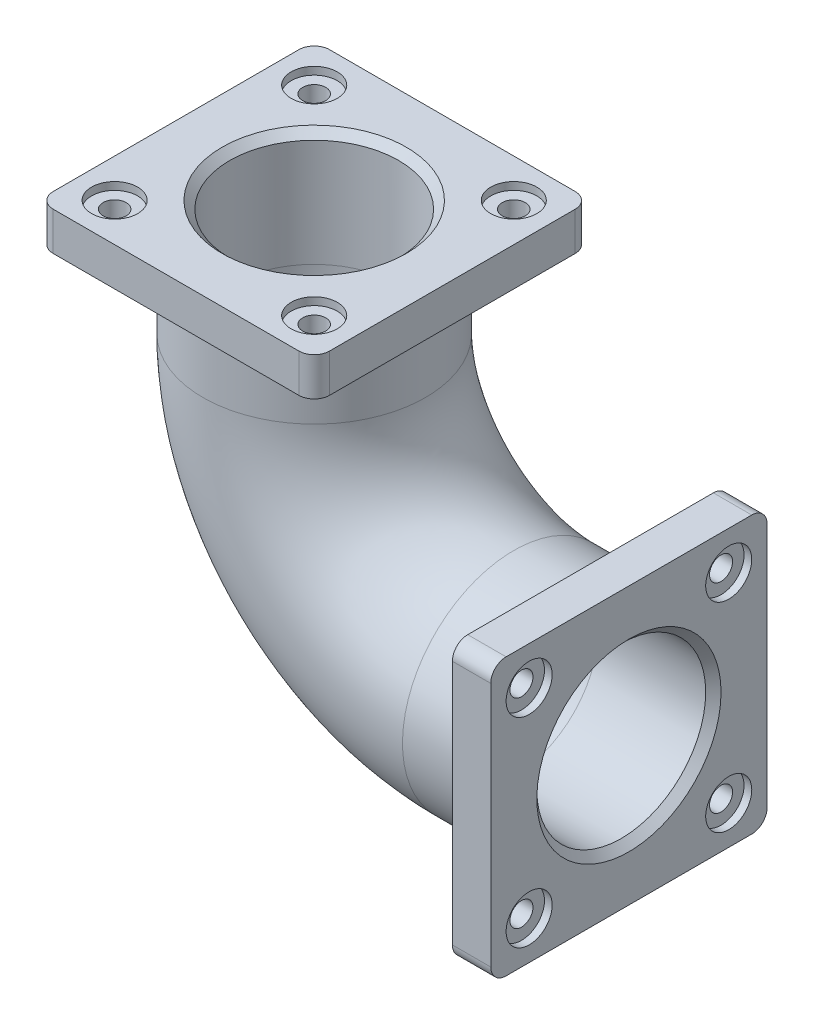
SolidWorks part; units mm, degrees
material "Malleable Cast Iron"
ref_plane "Front Plane" through (0, 0, 0) normal (0, 0, 1) x (1, 0, 0)
ref_plane "Top Plane" through (0, 0, 0) normal (0, 1, 0) x (1, 0, 0)
ref_plane "Right Plane" through (0, 0, 0) normal (1, 0, 0) x (0, 0, -1)
sketch "Sketch1" plane through (0, 0, 0) normal (0, 0, 1) x (1, 0, 0)
  line L0 (0, 0) -> (-150, 0)
  line L1 (-410, 260) -> (-410, 410)
  arc A0 (-150, 0) -> (-410, 260) centre (-150, 260) cw
sketch "Sketch2" plane through (0, 0, 0) normal (1, 0, 0) x (0, 0, -1)
  circle A0 centre (0, 0) radius 145
  circle A1 centre (0, 0) radius 110
sweep "Sweep12" add profiles "Sketch2" path "Sketch1"
sketch "Sketch8" plane through (0, 0, 0) normal (1, 0, 0) x (0, 0, -1)
  line L1 (-180, 180) -> (180, 180)
  line L2 (-180, 180) -> (-180, -180)
  line L3 (-180, -180) -> (180, -180)
  line L4 (180, 180) -> (180, -180)
  line L5 (-180, 180) -> (180, -180) construction
  line L6 (-180, -180) -> (180, 180) construction
  line L7 (-130, 130) -> (130, 130) construction
  line L8 (-130, 130) -> (-130, -130) construction
  line L9 (-130, -130) -> (130, -130) construction
  line L10 (130, 130) -> (130, -130) construction
  line L11 (-130, 130) -> (130, -130) construction
  line L12 (-130, -130) -> (130, 130) construction
  point P0 (0, 0)
  point P6 (0, 0)
  circle M10 centre (0, 0) radius 145
extrude "Boss-Extrude2" add sketch "Sketch8" against normal blind 50 contours L4 L1 L2 L3 M10
fillet "Fillet1" radius 20 4 edges at (-25, -180, -180) (-25, -180, 180) (-25, 180, -180) (-25, 180, 180)
hole_wizard "CBORE for #0 Binding Head Machine Screw3" positions "Sketch13" profile "Sketch15" counterbore size "#0" standard "ANSI Inch"
sketch "Sketch13" plane through (0, 0, 0) normal (1, 0, 0) x (0, 0, -1)
  point P0 (-130, 130)
  point P3 (130, 130)
  point P6 (130, -130)
  point P9 (-130, -130)
sketch "Sketch15" plane through (0, 130, 130) normal (0, 1, 0) x (0, 0, -1)
  line L0 (0, 0) -> (0, 50)
  line L1 (0, 50) -> (15, 50)
  line L3 (15, 50) -> (15, 10)
  line L4 (15, 10) -> (30, 10)
  line L5 (30, 10) -> (30, 0)
  line L7 (30, 0) -> (0, 0)
  line L11 (0, -6.35) -> (0, 107.95) construction
  dimension "Thru Hole Dia." = 30
  dimension "Thru Hole Depth" = 50
  dimension "C'Bore Dia." = 60
  dimension "C'Bore Depth" = 10
sketch "Sketch16" plane through (0, 410, 0) normal (0, 1, 0) x (1, 0, 0)
  line L0 (-410, -145) -> (-150, -145) construction
  line L1 (-590, 180) -> (-230, 180)
  line L2 (-590, 180) -> (-590, -180)
  line L3 (-590, -180) -> (-230, -180)
  line L4 (-230, 180) -> (-230, -180)
  line L5 (-590, 180) -> (-230, -180) construction
  line L6 (-590, -180) -> (-230, 180) construction
  line L7 (-555, 145) -> (-265, 145) construction
  line L8 (-555, 145) -> (-555, -145) construction
  line L9 (-555, -145) -> (-265, -145) construction
  line L10 (-265, 145) -> (-265, -145) construction
  line L11 (-555, 145) -> (-265, -145) construction
  line L12 (-555, -145) -> (-265, 145) construction
  point P0 (-410, 0)
  point P6 (-410, 0)
sketch "Sketch21" plane through (0, 410, 0) normal (0, 1, 0) x (1, 0, 0)
  line L1 (-590, 180) -> (-230, 180)
  line L2 (-590, 180) -> (-590, -180)
  line L3 (-590, -180) -> (-230, -180)
  line L4 (-230, 180) -> (-230, -180)
  line L5 (-590, 180) -> (-230, -180) construction
  line L6 (-590, -180) -> (-230, 180) construction
  line L7 (-540, 130) -> (-280, 130) construction
  line L8 (-540, 130) -> (-540, -130) construction
  line L9 (-540, -130) -> (-280, -130) construction
  line L10 (-280, 130) -> (-280, -130) construction
  line L11 (-540, 130) -> (-280, -130) construction
  line L12 (-540, -130) -> (-280, 130) construction
  point P0 (-410, 0)
  point P6 (-410, 0)
  circle M10 centre (-410, 0) radius 145
extrude "Boss-Extrude4" add sketch "Sketch21" against normal blind 50 contours L4 L1 L2 L3 M10
hole_wizard "CBORE for #0 Binding Head Machine Screw5" positions "Sketch26" profile "Sketch27" counterbore size "#0" standard "ANSI Inch"
sketch "Sketch26" plane through (0, 410, 0) normal (0, 1, 0) x (1, 0, 0)
  point P0 (-540, 130)
  point P3 (-280, 130)
  point P6 (-280, -130)
  point P9 (-540, -130)
sketch "Sketch27" plane through (-540, 410, -130) normal (1, 0, 0) x (0, 0, 1)
  line L0 (0, 0) -> (0, 50)
  line L1 (0, 50) -> (15, 50)
  line L3 (15, 50) -> (15, 10)
  line L4 (15, 10) -> (30, 10)
  line L5 (30, 10) -> (30, 0)
  line L7 (30, 0) -> (0, 0)
  line L11 (0, -6.35) -> (0, 107.95) construction
  dimension "Thru Hole Dia." = 30
  dimension "Thru Hole Depth" = 50
  dimension "C'Bore Dia." = 60
  dimension "C'Bore Depth" = 10
fillet "Fillet2" radius 20 4 edges at (-590, 385, -180) (-230, 385, -180) (-230, 385, 180) (-590, 385, 180)
chamfer "Chamfer1" distance 10 angle 45 2 edges at (0, 0, -110) (-410, 410, -110)
